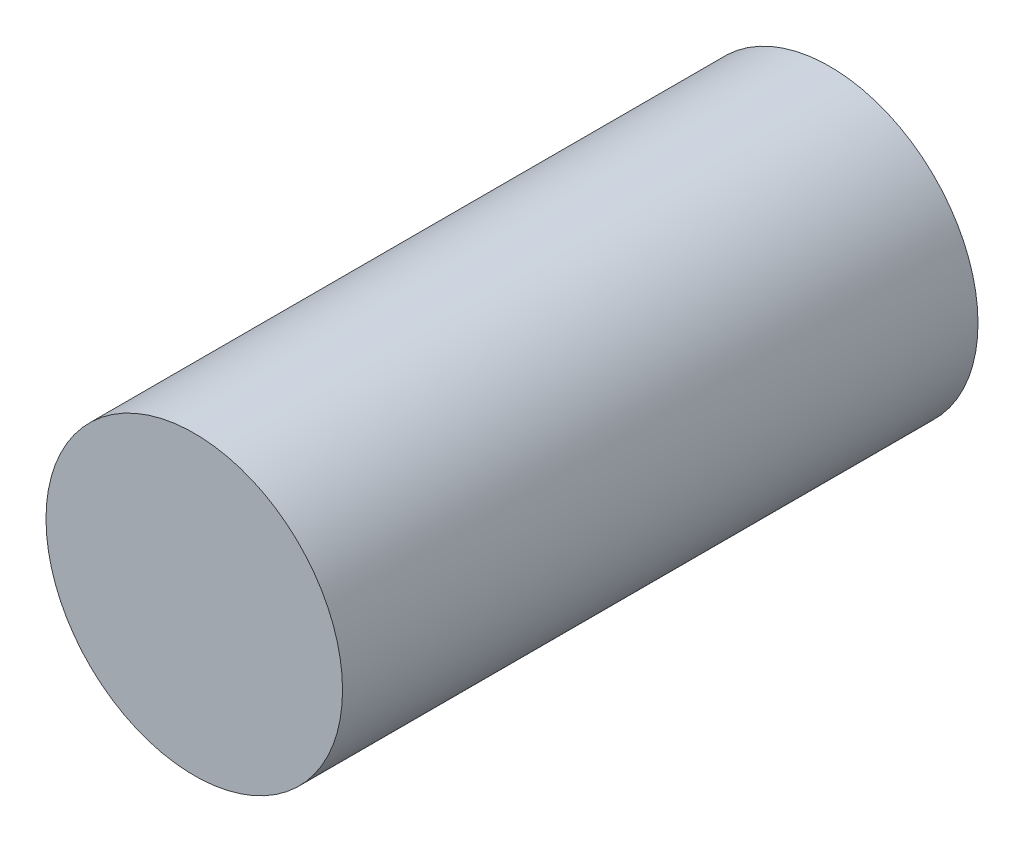
SolidWorks part; units mm, degrees
material "AISI 4340 Steel, normalized"
ref_plane "Front Plane" through (0, 0, 0) normal (0, 0, 1) x (1, 0, 0)
ref_plane "Top Plane" through (0, 0, 0) normal (0, 1, 0) x (1, 0, 0)
ref_plane "Right Plane" through (0, 0, 0) normal (1, 0, 0) x (0, 0, -1)
sketch "Sketch1" plane through (0, 0, 0) normal (0, 0, 1) x (1, 0, 0)
  circle A0 centre (0, 0) radius 7
extrude "Motor_Rotor_Output_Envelope" add sketch "Sketch1" along normal blind 30
